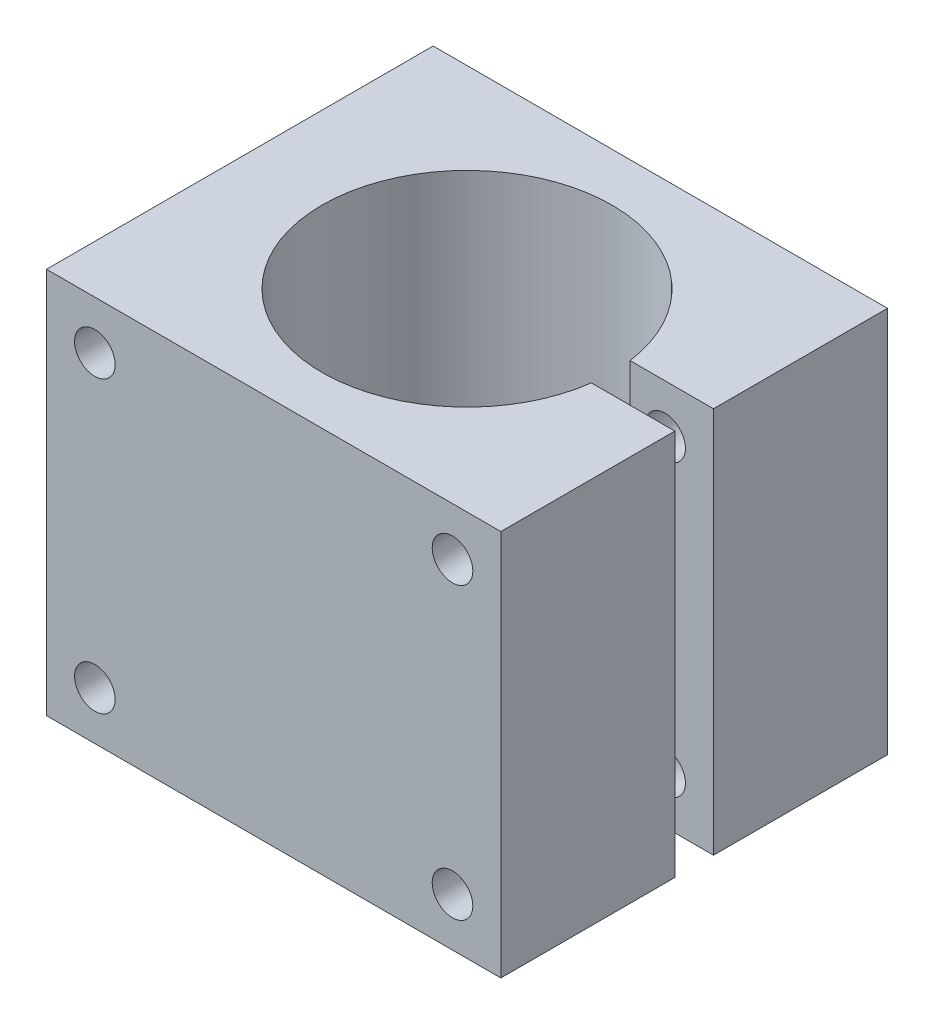
SolidWorks part; units mm, degrees
ref_plane "Front Plane" through (0, 0, 0) normal (0, 0, 1) x (1, 0, 0)
ref_plane "Top Plane" through (0, 0, 0) normal (0, 1, 0) x (1, 0, 0)
ref_plane "Right Plane" through (0, 0, 0) normal (1, 0, 0) x (0, 0, -1)
sketch "Sketch1" plane through (0, 0, 0) normal (0, 0, 1) x (1, 0, 0)
  line L0 (18.5, 35) -> (18.5, 16.2042) construction
  line L1 (-5, -5) -> (42, -5)
  line L2 (-5, -5) -> (-5, 35)
  line L3 (-5, 35) -> (42, 35)
  line L4 (42, -5) -> (42, 35)
  line L5 (-5, 15) -> (42, 15) construction
  circle A0 centre (0, 0) radius 2.1
  circle A1 centre (37, 0) radius 2.1
  circle A2 centre (0, 30) radius 2.1
  circle A3 centre (37, 30) radius 2.1
  dimension "D1" = 4.2
  dimension "D2" = 40
  dimension "D4" = 30
  dimension "D5" = 37
  dimension "D3" = 47
extrude "Boss-Extrude1" add sketch "Sketch1" along normal blind 40
sketch "Sketch6" plane through (0, 35, 0) normal (0, 1, 0) x (1, 0, 0)
  line L0 (42, -20) -> (-5, -20) construction
  line L1 (18.5, 0) -> (18.5, -40) construction
  line L4 (42, 0) -> (-5, 0)
  line L5 (-5, 0) -> (-5, -40)
  line L6 (-5, -40) -> (42, -40)
  line L7 (42, -40) -> (42, 0)
  line L8 (42, 0) -> (-5, 0)
  line L9 (-5, 0) -> (-5, -40)
  line L10 (-5, -40) -> (42, -40)
  line L11 (42, -40) -> (42, 0)
  circle A0 centre (18.5, -20) radius 15
  dimension "D2" = 30
  dimension "D1" = 0
extrude "Cut-Extrude5" cut sketch "Sketch6" against normal through all flip side to cut
sketch "Sketch7" plane through (0, 35, 0) normal (0, 1, 0) x (1, 0, 0)
  line L0 (42, -20) -> (-5, -20) construction
  line L1 (42, -18) -> (33.3661, -18)
  line L2 (42, -22) -> (33.3661, -22)
  line L4 (42, 0) -> (-5, 0)
  line L5 (-5, 0) -> (-5, -40)
  line L6 (-5, -40) -> (42, -40)
  line L7 (42, -40) -> (42, 0)
  line L8 (42, 0) -> (-5, 0)
  line L9 (-5, 0) -> (-5, -40)
  line L10 (-5, -40) -> (42, -40)
  line L11 (42, -40) -> (42, 0)
  circle A0 centre (18.5, -20) radius 15 construction
  circle M5 centre (18.5, -20) radius 15
  line M9 (42, -40) -> (42, 0)
  dimension "D2" = 4
  dimension "D1" = 0
extrude "Cut-Extrude6" cut sketch "Sketch7" against normal through all contours L0 L11 L1 M5 | L0 L2 M9 M5
